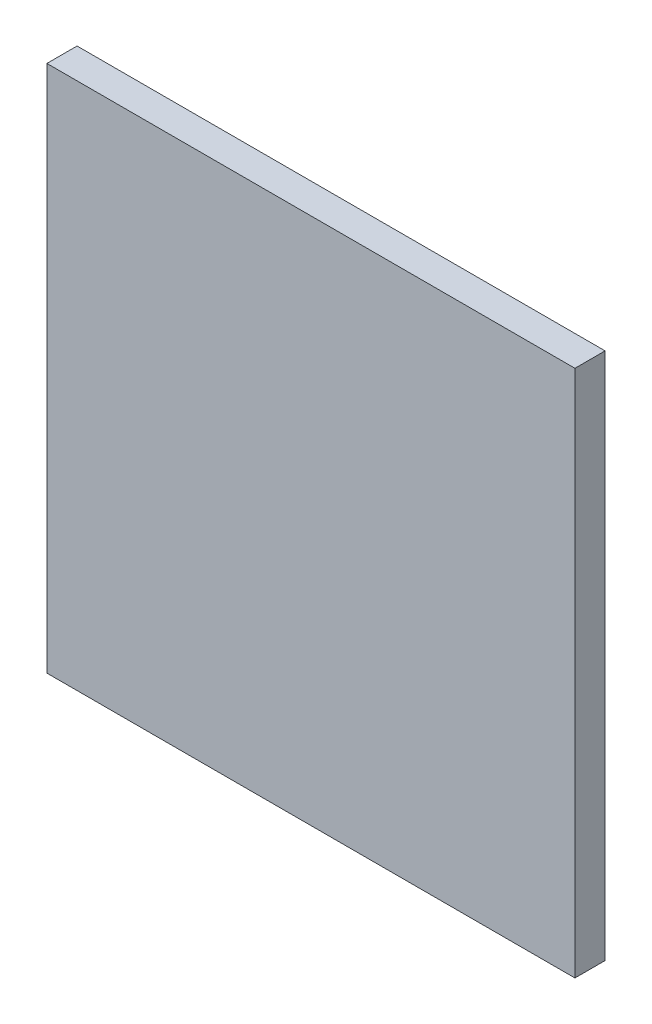
SolidWorks part; units mm, degrees
ref_plane "Front Plane" through (0, 0, 0) normal (0, 0, 1) x (1, 0, 0)
ref_plane "Top Plane" through (0, 0, 0) normal (0, 1, 0) x (1, 0, 0)
ref_plane "Right Plane" through (0, 0, 0) normal (1, 0, 0) x (0, 0, -1)
sketch "Sketch1" plane through (0, 0, 0) normal (0, 0, 1) x (1, 0, 0)
  line L1 (0, 0) -> (350, 0)
  line L2 (0, 0) -> (0, 350)
  line L3 (0, 350) -> (350, 350)
  line L4 (350, 0) -> (350, 350)
  dimension "D1" = 350
  dimension "D2" = 350
extrude "Boss-Extrude1" add sketch "Sketch1" along normal blind 20
sketch "Sketch2" plane through (0, 0, 20) normal (0, 0, 1) x (1, 0, 0)
  line L0 (350, 0) -> (350, 350) construction
  line L1 (350, 160) -> (0, 160)
  line L2 (350, 160) -> (350, 190)
  line L3 (350, 190) -> (0, 190)
  line L4 (0, 160) -> (0, 190)
  line L5 (0, 350) -> (0, 0) construction
  dimension "D1" = 30
  dimension "D2" = 160
